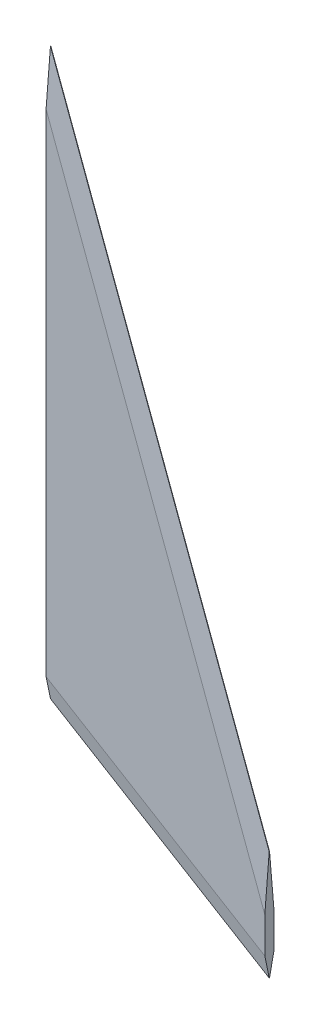
SolidWorks part; units mm, degrees
material "CF (correct density)"
ref_plane "Front Plane" through (0, 0, 0) normal (0, 0, 1) x (1, 0, 0)
ref_plane "Top Plane" through (0, 0, 0) normal (0, 1, 0) x (1, 0, 0)
ref_plane "Right Plane" through (0, 0, 0) normal (1, 0, 0) x (0, 0, -1)
sketch "Sketch2" plane through (0, 0, 0) normal (0, 0, 1) x (1, 0, 0)
  line L0 (0, 0) -> (0, 393.7)
  line L1 (0, 393.7) -> (152.414, -16.129)
  line L2 (152.414, -16.129) -> (152.414, -92.329)
  line L3 (152.414, -92.329) -> (0, 0)
  dimension "D1" = 393.7
  dimension "D2" = 76.2
  dimension "D3" = 409.829
  dimension "D4" = 20.4
extrude "Boss-Extrude1" add sketch "Sketch2" along normal blind 6.35
chamfer "Chamfer1" distance 12.7 distance2 3.048 2 edges at (76.207, -46.1645, 0) (76.207, 188.7855, 0)
chamfer "Chamfer2" distance 3.048 distance2 12.7 2 edges at (76.207, -46.1645, 6.35) (76.207, 188.7855, 6.35)
